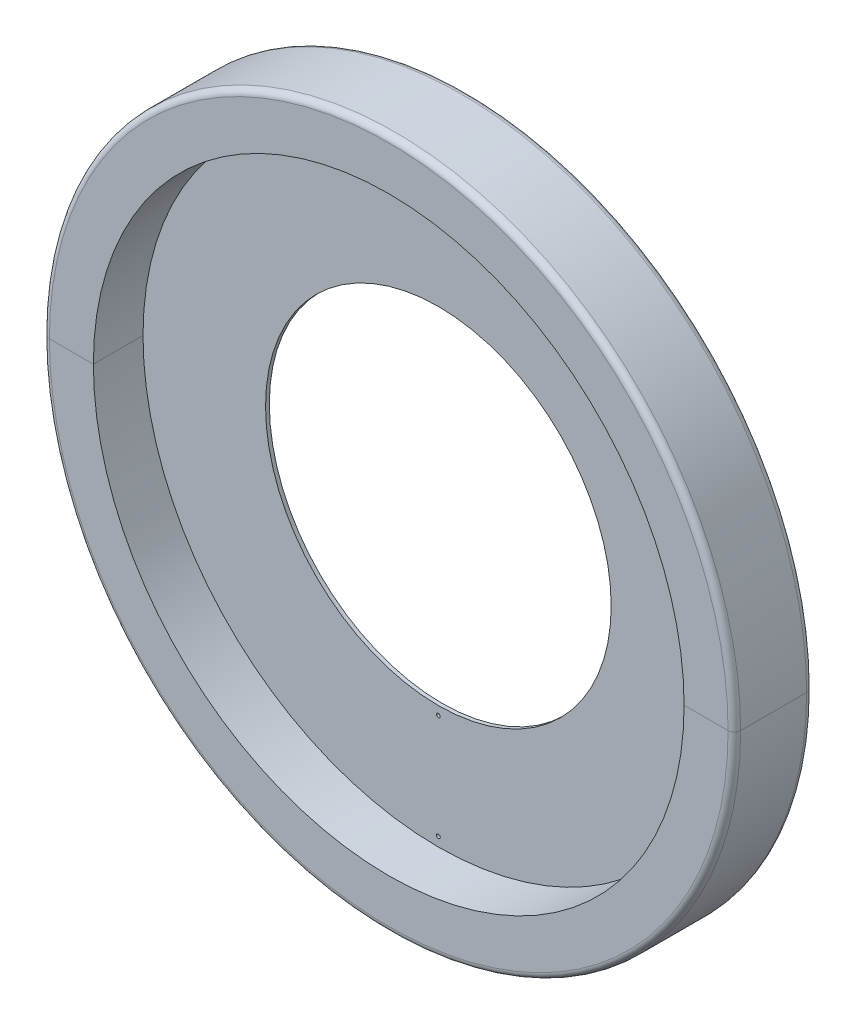
SolidWorks part; units mm, degrees
ref_plane "Plano frontal" through (0, 0, 0) normal (0, 0, 1) x (1, 0, 0)
ref_plane "Plano superior" through (0, 0, 0) normal (0, 1, 0) x (1, 0, 0)
ref_plane "Plano direito" through (0, 0, 0) normal (1, 0, 0) x (0, 0, -1)
sketch "Esboço1" plane through (0, 0, 0) normal (0, 0, 1) x (1, 0, 0)
  circle A0 centre (0, 0) radius 470
  dimension "D1" = 940
extrude "Ressalto-extrusão1" add sketch "Esboço1" along normal blind 6
sketch "Esboço2" plane through (0, 0, 6) normal (0, 0, 1) x (1, 0, 0)
  circle A0 centre (0, 0) radius 275
  dimension "D1" = 550
extrude "Corte-extrusão1" cut sketch "Esboço2" against normal blind 6
sketch "Esboço3" plane through (0, 0, 6) normal (0, 0, 1) x (1, 0, 0)
  line L0 (0, -455) -> (0, -275) construction
  circle A0 centre (0, -455) radius 3
  circle A1 centre (0, 0) radius 275 construction
  circle A2 centre (0, -288.71) radius 3
  dimension "D1" = 6
  dimension "D3" = 6
  dimension "D4" = 166.29
  dimension "D2" = 180
extrude "Corte-extrusão2" cut sketch "Esboço3" against normal blind 6
sketch "Esboço4" plane through (0, 0, 0) normal (0, 1, 0) x (1, 0, 0)
  line L0 (-470, 0) -> (-470, 40)
  line L1 (-470, 40) -> (-540, 40)
  line L2 (-550, 30) -> (-550, -75)
  line L3 (-540, -85) -> (-470, -85)
  line L4 (-470, -85) -> (-470, 0)
  arc A0 (-550, 30) -> (-540, 40) centre (-540, 30) cw
  arc A1 (-550, -75) -> (-540, -85) centre (-540, -75) ccw
  point P8 (-550, 40)
  point P11 (-550, -85)
  dimension "D4" = 10
  dimension "D5" = 10
  dimension "D1" = 80
  dimension "D2" = 125
  dimension "D3" = 40
sweep "Varredura1" add profiles "Esboço4" path edge at (470, 0, 0)
